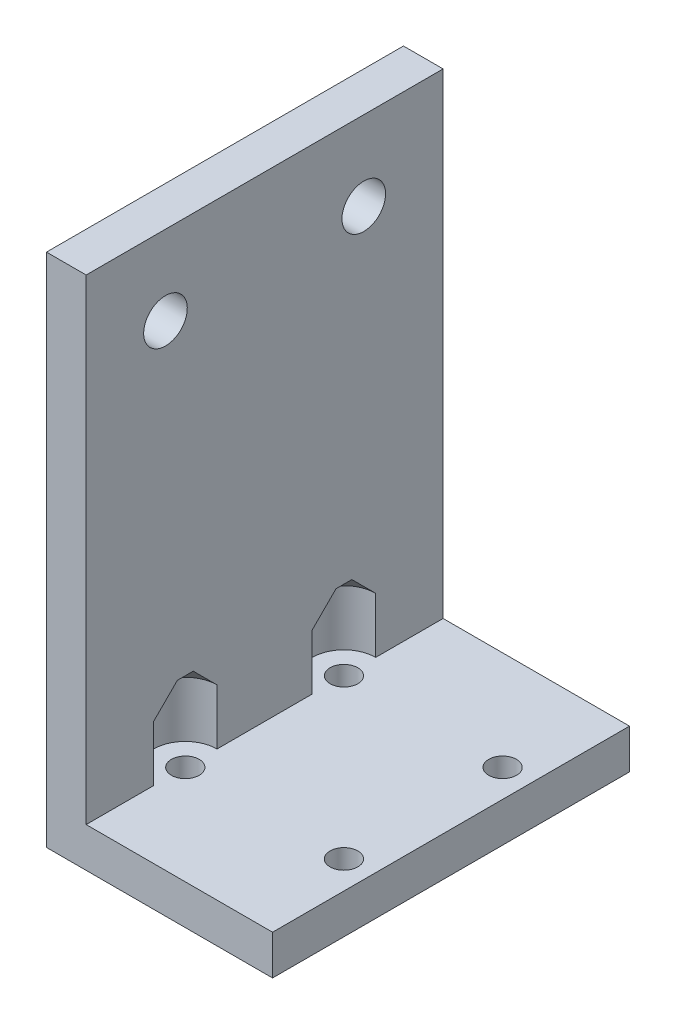
SolidWorks part; units mm, degrees
ref_plane "Plan de face" through (0, 0, 0) normal (0, 0, 1) x (1, 0, 0)
ref_plane "Plan de dessus" through (0, 0, 0) normal (0, 1, 0) x (1, 0, 0)
ref_plane "Plan de droite" through (0, 0, 0) normal (1, 0, 0) x (0, 0, -1)
sketch "Esquisse1" plane through (0, 0, 0) normal (0, 0, 1) x (1, 0, 0)
  line L0 (-32.9131, 0) -> (-4.4131, 0)
  line L1 (-4.4131, 0) -> (-4.4131, 5)
  line L11 (-32.9131, 65) -> (-32.9131, 0)
  line L12 (-4.4131, 5) -> (-27.9131, 5)
  line L17 (-27.9131, 5) -> (-27.9131, 65)
  line L21 (-27.9131, 65) -> (-32.9131, 65)
  point P3 (0, 0)
  point P6 (0, 0)
  dimension "D1" = 65
  dimension "D2" = 5
  dimension "D3" = 23.5
extrude "Boss.-Extru.1" add sketch "Esquisse1" along normal blind 45
sketch "Esquisse2" plane through (0, 5, 0) normal (0, 1, 0) x (1, 0, 0)
  line L0 (-27.9131, -32.5) -> (-7.9131, -32.5) construction
  line L1 (-7.9131, -32.5) -> (-7.9131, -12.5) construction
  line L2 (-4.4131, -45) -> (-4.4131, 0) construction
  circle A0 centre (-27.9131, -32.5) radius 1.75
  circle A1 centre (-27.9131, -12.5) radius 1.75
  circle A2 centre (-7.9131, -12.5) radius 1.75
  circle A3 centre (-7.9131, -32.5) radius 1.75
  point P8 (-7.9131, -22.5)
  point P11 (-4.4131, -22.5)
  dimension "D1" = 3.5
  dimension "D2" = 20
  dimension "D3" = 3.5
extrude "Enlèv. mat.-Extru.1" cut sketch "Esquisse2" against normal up to next
sketch "Esquisse3" plane through (-32.9131, 0, 0) normal (-1, 0, 0) x (0, 0, 1)
  line L0 (0, 65) -> (0, 0) construction
  line L1 (45, 65) -> (0, 65) construction
  line L2 (45, 65) -> (45, 0) construction
  circle A0 centre (10, 55) radius 2.75
  circle A1 centre (35, 55) radius 2.75
  point P4 (0, 0)
  dimension "D1" = 5.5
  dimension "D2" = 10
  dimension "D3" = 10
  dimension "D4" = 10
extrude "Enlèv. mat.-Extru.2" cut sketch "Esquisse3" against normal up to next
sketch "Esquisse4" plane through (0, 5, 0) normal (0, 1, 0) x (1, 0, 0)
  line L0 (-27.9131, -34.25) -> (-27.9131, -30.75) construction
  line L1 (-27.9131, -14.25) -> (-27.9131, -10.75) construction
  circle A0 centre (-27.9131, -32.5) radius 4
  circle A1 centre (-27.9131, -12.5) radius 4
  dimension "D1" = 8
extrude "Enlèv. mat.-Extru.3" cut sketch "Esquisse4" along normal blind 10
chamfer "Chanfrein1" distance 3 angle 45 2 edges at (-31.9131, 15, 12.5) (-31.9131, 15, 32.5)
